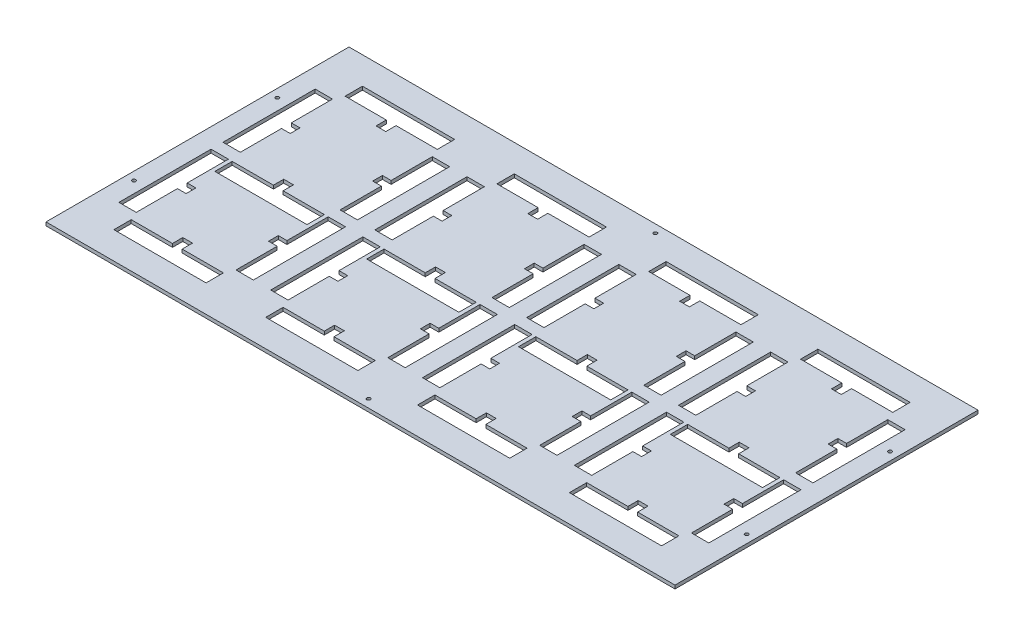
SolidWorks part; units mm, degrees
ref_plane "Front Plane" through (0, 0, 0) normal (0, 0, 1) x (1, 0, 0)
ref_plane "Top Plane" through (0, 0, 0) normal (0, 1, 0) x (1, 0, 0)
ref_plane "Right Plane" through (0, 0, 0) normal (1, 0, 0) x (0, 0, -1)
sketch "Sketch1" plane through (0, 0, 0) normal (0, 1, 0) x (1, 0, 0)
  line L0 (0, 139.7) -> (0, -139.7) construction
  line L1 (-290, 139.7) -> (290, 139.7)
  line L2 (-290, 139.7) -> (-290, -139.7)
  line L3 (-290, -139.7) -> (290, -139.7)
  line L4 (290, 139.7) -> (290, -139.7)
  line L5 (-290, 139.7) -> (290, -139.7) construction
  line L6 (-290, -139.7) -> (290, 139.7) construction
  line L7 (-282.5, 132.2) -> (282.5, 132.2) construction
  line L8 (-282.5, 132.2) -> (-282.5, -132.2) construction
  line L9 (-282.5, -132.2) -> (282.5, -132.2) construction
  line L10 (282.5, 132.2) -> (282.5, -132.2) construction
  line L11 (-282.5, 132.2) -> (282.5, -132.2) construction
  line L12 (-282.5, -132.2) -> (282.5, 132.2) construction
  line L13 (-290, 0) -> (290, 0) construction
  line L14 (282.5, 132.2) -> (282.5, -132.2) construction
  circle A0 centre (-282.5, 66.1) radius 1.65
  circle A3 centre (-282.5, -66.1) radius 1.65
  circle A10 centre (282.5, -66.1) radius 1.65
  circle A11 centre (282.5, 66.1) radius 1.65
  circle A12 centre (0, 132.2) radius 1.65
  circle A13 centre (0, -132.2) radius 1.65
  point P0 (0, 0)
  point P6 (0, 0)
  dimension "D5" = 3.3
  dimension "D12" = 3.3
  dimension "D13" = 3.3
  dimension "D1" = 580
  dimension "D2" = 279.4
  dimension "D3" = 7.5
  dimension "D4" = 7.5
  dimension "D8" = 66.1
extrude "Boss-Extrude1" add sketch "Sketch1" along normal blind 3.175
sketch "Sketch2" plane through (0, 3.175, 0) normal (0, 1, 0) x (1, 0, 0)
  line L0 (0, 139.7) -> (0, -139.7) construction
  line L1 (290, 139.7) -> (-290, 139.7) construction
  line L2 (-290, -139.7) -> (290, -139.7) construction
  line L3 (-190, 139.7) -> (-190, -139.7) construction
  line L4 (-252, 139.7) -> (-252, -139.7) construction
  line L5 (-290, 0) -> (290, 0) construction
  line L6 (-290, 139.7) -> (-290, -139.7) construction
  line L7 (290, -139.7) -> (290, 139.7) construction
  line L8 (-248, 52.5) -> (-256, 52.5)
  line L12 (-248, 52.5) -> (-248, 43.5)
  line L13 (-210, 139.7) -> (-210, -139.7) construction
  line L14 (-164, 43.5) -> (-164, 5.5)
  line L15 (-272, 90.5) -> (-256, 90.5)
  line L16 (-272, 90.5) -> (-272, 5.5)
  line L17 (-272, 5.5) -> (-256, 5.5)
  line L19 (-172, 43.5) -> (-164, 43.5)
  line L20 (-164, 52.5) -> (-164, 90.5)
  line L21 (-256, 52.5) -> (-256, 90.5)
  line L22 (-248, 43.5) -> (-256, 43.5)
  line L23 (-256, 43.5) -> (-256, 5.5)
  line L24 (-148, 5.5) -> (-164, 5.5)
  line L25 (-148, 90.5) -> (-148, 5.5)
  line L26 (-148, 90.5) -> (-164, 90.5)
  line L27 (-172, 52.5) -> (-172, 43.5)
  line L28 (-172, 52.5) -> (-164, 52.5)
  line L29 (-172, -52.5) -> (-164, -52.5)
  line L30 (-172, -52.5) -> (-172, -43.5)
  line L31 (-148, -90.5) -> (-164, -90.5)
  line L32 (-148, -90.5) -> (-148, -5.5)
  line L33 (-148, -5.5) -> (-164, -5.5)
  line L34 (-256, -43.5) -> (-256, -5.5)
  line L35 (-248, -43.5) -> (-256, -43.5)
  line L36 (-256, -52.5) -> (-256, -90.5)
  line L37 (-164, -52.5) -> (-164, -90.5)
  line L38 (-172, -43.5) -> (-164, -43.5)
  line L39 (-272, -5.5) -> (-256, -5.5)
  line L40 (-272, -90.5) -> (-272, -5.5)
  line L41 (-272, -90.5) -> (-256, -90.5)
  line L42 (-164, -43.5) -> (-164, -5.5)
  line L43 (-248, -52.5) -> (-248, -43.5)
  line L44 (-248, -52.5) -> (-256, -52.5)
  line L45 (-214.5, 4) -> (-205.5, 4)
  line L46 (-205.5, 4) -> (-205.5, -5.5)
  line L47 (-205.5, -5.5) -> (-167.5, -5.5)
  line L48 (-167.5, -5.5) -> (-167.5, -21.5)
  line L49 (-167.5, -21.5) -> (-252.5, -21.5)
  line L50 (-252.5, -21.5) -> (-252.5, -5.5)
  line L51 (-252.5, -5.5) -> (-214.5, -5.5)
  line L52 (-214.5, -5.5) -> (-214.5, 4)
  line L53 (-290, 46.55) -> (290, 46.55) construction
  line L54 (-214.5, 98.6) -> (-214.5, 89.1)
  line L55 (-252.5, 98.6) -> (-214.5, 98.6)
  line L56 (-252.5, 114.6) -> (-252.5, 98.6)
  line L57 (-167.5, 114.6) -> (-252.5, 114.6)
  line L58 (-167.5, 98.6) -> (-167.5, 114.6)
  line L59 (-205.5, 98.6) -> (-167.5, 98.6)
  line L60 (-205.5, 89.1) -> (-205.5, 98.6)
  line L61 (-214.5, 89.1) -> (-205.5, 89.1)
  line L62 (-214.5, -89.1) -> (-205.5, -89.1)
  line L63 (-205.5, -89.1) -> (-205.5, -98.6)
  line L64 (-205.5, -98.6) -> (-167.5, -98.6)
  line L65 (-167.5, -98.6) -> (-167.5, -114.6)
  line L66 (-167.5, -114.6) -> (-252.5, -114.6)
  line L67 (-252.5, -114.6) -> (-252.5, -98.6)
  line L68 (-252.5, -98.6) -> (-214.5, -98.6)
  line L69 (-214.5, -98.6) -> (-214.5, -89.1)
  line L70 (-140, 139.7) -> (-140, -139.7) construction
  line L71 (-65.5, -98.6) -> (-65.5, -89.1)
  line L72 (-27.5, -98.6) -> (-65.5, -98.6)
  line L73 (-27.5, -114.6) -> (-27.5, -98.6)
  line L74 (-112.5, -114.6) -> (-27.5, -114.6)
  line L75 (-112.5, -98.6) -> (-112.5, -114.6)
  line L76 (-74.5, -98.6) -> (-112.5, -98.6)
  line L77 (-74.5, -89.1) -> (-74.5, -98.6)
  line L78 (-65.5, -89.1) -> (-74.5, -89.1)
  line L79 (-65.5, 89.1) -> (-74.5, 89.1)
  line L80 (-74.5, 89.1) -> (-74.5, 98.6)
  line L81 (-74.5, 98.6) -> (-112.5, 98.6)
  line L82 (-112.5, 98.6) -> (-112.5, 114.6)
  line L83 (-112.5, 114.6) -> (-27.5, 114.6)
  line L84 (-27.5, 114.6) -> (-27.5, 98.6)
  line L85 (-27.5, 98.6) -> (-65.5, 98.6)
  line L86 (-65.5, 98.6) -> (-65.5, 89.1)
  line L87 (-65.5, -5.5) -> (-65.5, 4)
  line L88 (-27.5, -5.5) -> (-65.5, -5.5)
  line L89 (-27.5, -21.5) -> (-27.5, -5.5)
  line L90 (-112.5, -21.5) -> (-27.5, -21.5)
  line L91 (-112.5, -5.5) -> (-112.5, -21.5)
  line L92 (-74.5, -5.5) -> (-112.5, -5.5)
  line L93 (-74.5, 4) -> (-74.5, -5.5)
  line L94 (-65.5, 4) -> (-74.5, 4)
  line L95 (-32, -52.5) -> (-24, -52.5)
  line L96 (-32, -52.5) -> (-32, -43.5)
  line L97 (-116, -43.5) -> (-116, -5.5)
  line L98 (-8, -90.5) -> (-24, -90.5)
  line L99 (-8, -90.5) -> (-8, -5.5)
  line L100 (-8, -5.5) -> (-24, -5.5)
  line L101 (-108, -43.5) -> (-116, -43.5)
  line L102 (-116, -52.5) -> (-116, -90.5)
  line L103 (-24, -52.5) -> (-24, -90.5)
  line L104 (-32, -43.5) -> (-24, -43.5)
  line L105 (-24, -43.5) -> (-24, -5.5)
  line L106 (-132, -5.5) -> (-116, -5.5)
  line L107 (-132, -90.5) -> (-132, -5.5)
  line L108 (-132, -90.5) -> (-116, -90.5)
  line L109 (-108, -52.5) -> (-108, -43.5)
  line L110 (-108, -52.5) -> (-116, -52.5)
  line L111 (-108, 52.5) -> (-116, 52.5)
  line L112 (-108, 52.5) -> (-108, 43.5)
  line L113 (-132, 90.5) -> (-116, 90.5)
  line L114 (-132, 90.5) -> (-132, 5.5)
  line L115 (-132, 5.5) -> (-116, 5.5)
  line L116 (-24, 43.5) -> (-24, 5.5)
  line L117 (-32, 43.5) -> (-24, 43.5)
  line L118 (-24, 52.5) -> (-24, 90.5)
  line L119 (-116, 52.5) -> (-116, 90.5)
  line L120 (-108, 43.5) -> (-116, 43.5)
  line L121 (-8, 5.5) -> (-24, 5.5)
  line L122 (-8, 90.5) -> (-8, 5.5)
  line L123 (-8, 90.5) -> (-24, 90.5)
  line L124 (-116, 43.5) -> (-116, 5.5)
  line L125 (-32, 52.5) -> (-32, 43.5)
  line L126 (-32, 52.5) -> (-24, 52.5)
  line L127 (32, 52.5) -> (24, 52.5)
  line L128 (32, 52.5) -> (32, 43.5)
  line L129 (116, 43.5) -> (116, 5.5)
  line L130 (8, 90.5) -> (24, 90.5)
  line L131 (8, 90.5) -> (8, 5.5)
  line L132 (8, 5.5) -> (24, 5.5)
  line L133 (108, 43.5) -> (116, 43.5)
  line L134 (116, 52.5) -> (116, 90.5)
  line L135 (24, 52.5) -> (24, 90.5)
  line L136 (32, 43.5) -> (24, 43.5)
  line L137 (24, 43.5) -> (24, 5.5)
  line L138 (132, 5.5) -> (116, 5.5)
  line L139 (132, 90.5) -> (132, 5.5)
  line L140 (132, 90.5) -> (116, 90.5)
  line L141 (108, 52.5) -> (108, 43.5)
  line L142 (108, 52.5) -> (116, 52.5)
  line L143 (108, -52.5) -> (116, -52.5)
  line L144 (108, -52.5) -> (108, -43.5)
  line L145 (132, -90.5) -> (116, -90.5)
  line L146 (132, -90.5) -> (132, -5.5)
  line L147 (132, -5.5) -> (116, -5.5)
  line L148 (24, -43.5) -> (24, -5.5)
  line L149 (32, -43.5) -> (24, -43.5)
  line L150 (24, -52.5) -> (24, -90.5)
  line L151 (116, -52.5) -> (116, -90.5)
  line L152 (108, -43.5) -> (116, -43.5)
  line L153 (8, -5.5) -> (24, -5.5)
  line L154 (8, -90.5) -> (8, -5.5)
  line L155 (8, -90.5) -> (24, -90.5)
  line L156 (116, -43.5) -> (116, -5.5)
  line L157 (32, -52.5) -> (32, -43.5)
  line L158 (32, -52.5) -> (24, -52.5)
  line L159 (65.5, 4) -> (74.5, 4)
  line L160 (74.5, 4) -> (74.5, -5.5)
  line L161 (74.5, -5.5) -> (112.5, -5.5)
  line L162 (112.5, -5.5) -> (112.5, -21.5)
  line L163 (112.5, -21.5) -> (27.5, -21.5)
  line L164 (27.5, -21.5) -> (27.5, -5.5)
  line L165 (27.5, -5.5) -> (65.5, -5.5)
  line L166 (65.5, -5.5) -> (65.5, 4)
  line L167 (65.5, 98.6) -> (65.5, 89.1)
  line L168 (27.5, 98.6) -> (65.5, 98.6)
  line L169 (27.5, 114.6) -> (27.5, 98.6)
  line L170 (112.5, 114.6) -> (27.5, 114.6)
  line L171 (112.5, 98.6) -> (112.5, 114.6)
  line L172 (74.5, 98.6) -> (112.5, 98.6)
  line L173 (74.5, 89.1) -> (74.5, 98.6)
  line L174 (65.5, 89.1) -> (74.5, 89.1)
  line L175 (65.5, -89.1) -> (74.5, -89.1)
  line L176 (74.5, -89.1) -> (74.5, -98.6)
  line L177 (74.5, -98.6) -> (112.5, -98.6)
  line L178 (112.5, -98.6) -> (112.5, -114.6)
  line L179 (112.5, -114.6) -> (27.5, -114.6)
  line L180 (27.5, -114.6) -> (27.5, -98.6)
  line L181 (27.5, -98.6) -> (65.5, -98.6)
  line L182 (65.5, -98.6) -> (65.5, -89.1)
  line L183 (214.5, -98.6) -> (214.5, -89.1)
  line L184 (252.5, -98.6) -> (214.5, -98.6)
  line L185 (252.5, -114.6) -> (252.5, -98.6)
  line L186 (167.5, -114.6) -> (252.5, -114.6)
  line L187 (167.5, -98.6) -> (167.5, -114.6)
  line L188 (205.5, -98.6) -> (167.5, -98.6)
  line L189 (205.5, -89.1) -> (205.5, -98.6)
  line L190 (214.5, -89.1) -> (205.5, -89.1)
  line L191 (214.5, 89.1) -> (205.5, 89.1)
  line L192 (205.5, 89.1) -> (205.5, 98.6)
  line L193 (205.5, 98.6) -> (167.5, 98.6)
  line L194 (167.5, 98.6) -> (167.5, 114.6)
  line L195 (167.5, 114.6) -> (252.5, 114.6)
  line L196 (252.5, 114.6) -> (252.5, 98.6)
  line L197 (252.5, 98.6) -> (214.5, 98.6)
  line L198 (214.5, 98.6) -> (214.5, 89.1)
  line L199 (214.5, -5.5) -> (214.5, 4)
  line L200 (252.5, -5.5) -> (214.5, -5.5)
  line L201 (252.5, -21.5) -> (252.5, -5.5)
  line L202 (167.5, -21.5) -> (252.5, -21.5)
  line L203 (167.5, -5.5) -> (167.5, -21.5)
  line L204 (205.5, -5.5) -> (167.5, -5.5)
  line L205 (205.5, 4) -> (205.5, -5.5)
  line L206 (214.5, 4) -> (205.5, 4)
  line L207 (248, -52.5) -> (256, -52.5)
  line L208 (248, -52.5) -> (248, -43.5)
  line L209 (164, -43.5) -> (164, -5.5)
  line L210 (272, -90.5) -> (256, -90.5)
  line L211 (272, -90.5) -> (272, -5.5)
  line L212 (272, -5.5) -> (256, -5.5)
  line L213 (172, -43.5) -> (164, -43.5)
  line L214 (164, -52.5) -> (164, -90.5)
  line L215 (256, -52.5) -> (256, -90.5)
  line L216 (248, -43.5) -> (256, -43.5)
  line L217 (256, -43.5) -> (256, -5.5)
  line L218 (148, -5.5) -> (164, -5.5)
  line L219 (148, -90.5) -> (148, -5.5)
  line L220 (148, -90.5) -> (164, -90.5)
  line L221 (172, -52.5) -> (172, -43.5)
  line L222 (172, -52.5) -> (164, -52.5)
  line L223 (172, 52.5) -> (164, 52.5)
  line L224 (172, 52.5) -> (172, 43.5)
  line L225 (148, 90.5) -> (164, 90.5)
  line L226 (148, 90.5) -> (148, 5.5)
  line L227 (148, 5.5) -> (164, 5.5)
  line L228 (256, 43.5) -> (256, 5.5)
  line L229 (248, 43.5) -> (256, 43.5)
  line L230 (256, 52.5) -> (256, 90.5)
  line L231 (164, 52.5) -> (164, 90.5)
  line L232 (172, 43.5) -> (164, 43.5)
  line L233 (272, 5.5) -> (256, 5.5)
  line L234 (272, 90.5) -> (272, 5.5)
  line L235 (272, 90.5) -> (256, 90.5)
  line L236 (164, 43.5) -> (164, 5.5)
  line L237 (248, 52.5) -> (248, 43.5)
  line L238 (248, 52.5) -> (256, 52.5)
  point P16 (-248, 48)
  point P18 (-252, 52.5)
  point P36 (-172, 48)
  point P53 (-172, -48)
  point P54 (-248, -48)
  point P63 (-210, 4)
  point P140 (-32, -48)
  point P141 (-108, -48)
  point P142 (-108, 48)
  point P143 (-32, 48)
  point P256 (32, 48)
  point P257 (108, 48)
  point P258 (108, -48)
  point P259 (32, -48)
  point P260 (248, -48)
  point P261 (172, -48)
  point P262 (172, 48)
  point P263 (248, 48)
  dimension "D1" = 190
  dimension "D2" = 62
  dimension "D4" = 85
  dimension "D5" = 9
  dimension "D6" = 48
  dimension "D7" = 16
  dimension "D8" = 4
  dimension "D3" = 42
  dimension "D9" = 4
  dimension "D10" = 46.55
  dimension "D11" = 50
extrude "Cut-Extrude1" cut sketch "Sketch2" against normal up to surface (3.175 mm away) up to face at (0, 0, 0)
equation "\"D12@Sketch1\"=\"D5@Sketch1\""
equation "\"D13@Sketch1\"=\"D5@Sketch1\""
equation "\"D9@Sketch2\"=\"D8@Sketch2\""
